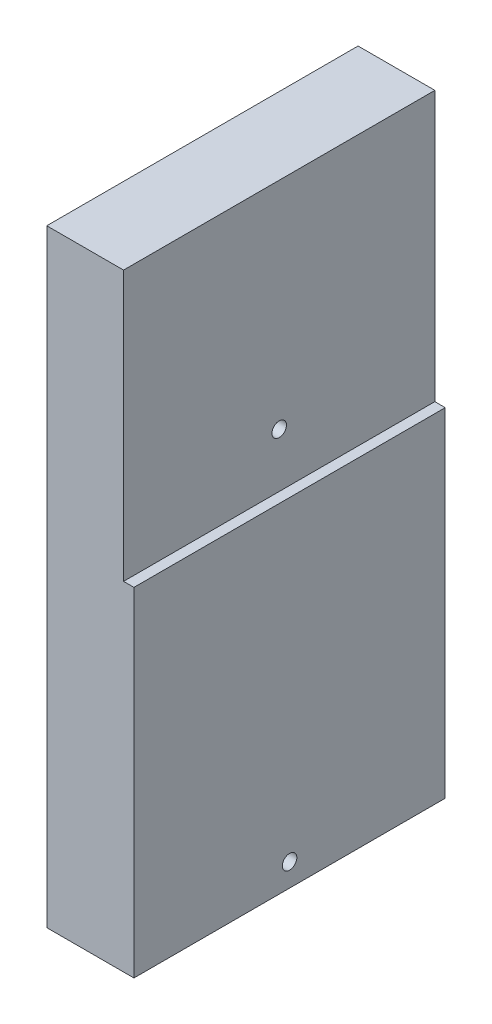
SolidWorks part; units mm, degrees
material "ABS"
ref_plane "Front Plane" through (0, 0, 0) normal (0, 0, 1) x (1, 0, 0)
ref_plane "Top Plane" through (0, 0, 0) normal (0, 1, 0) x (1, 0, 0)
ref_plane "Right Plane" through (0, 0, 0) normal (1, 0, 0) x (0, 0, -1)
sketch "Sketch1" plane through (0, 0, 0) normal (0, 0, 1) x (1, 0, 0)
  line L0 (-20, 159.45) -> (-20, 13)
  line L1 (0, 13) -> (1, 13)
  line L2 (1, 13) -> (1, 94.5)
  line L3 (1, 94.5) -> (-1.5, 94.5)
  line L4 (-1.5, 94.5) -> (-1.5, 159.45)
  line L5 (-1.5, 159.45) -> (-20, 159.45)
  line L6 (-20, 13) -> (0, 13)
  dimension "D2" = 1
  dimension "D3" = 81.5
  dimension "D4" = 2.5
extrude "Boss-Extrude1" add sketch "Sketch1" along normal blind 75
sketch "Sketch2" plane through (1, 0, 0) normal (1, 0, 0) x (0, 0, -1)
  line L0 (-75, 13) -> (0, 13) construction
  line L1 (-75, 13) -> (-75, 94.5) construction
  circle A0 centre (-37.5, 18.5) radius 1.75
  point P0 (-37.5, 18.5)
  point P1 (-37.5, 13)
  dimension "D3" = 3.5
  dimension "D1" = 5.5
  dimension "D2" = 37.5
extrude "Cut-Extrude1" cut sketch "Sketch2" against normal blind 25
sketch "Sketch4" plane through (-1.5, 0, 0) normal (1, 0, 0) x (0, 0, -1)
  line L0 (-75, 94.5) -> (0, 94.5) construction
  line L1 (-75, 94.5) -> (-75, 159.45) construction
  circle A0 centre (-37.5, 107.5) radius 1.75
  point P0 (-37.5, 107.5)
  dimension "D3" = 3.5
  dimension "D1" = 13
  dimension "D2" = 37.5
extrude "Cut-Extrude3" cut sketch "Sketch4" against normal blind 25 contours A0
sketch "Sketch5" plane through (0, 13, 0) normal (0, -1, 0) x (1, 0, 0)
  line L0 (-9.5, 75) -> (-9.5, 0) construction
  line L1 (-20, 75) -> (1, 75) construction
  line L2 (-20, 0) -> (1, 0) construction
  line L3 (-20, 75) -> (-20, 0) construction
  circle A0 centre (-9.5, 50) radius 2.1
  circle A1 centre (-9.5, 25) radius 2.1
  point P6 (-9.5, 50)
  point P7 (-9.5, 25)
  dimension "D3" = 4.2
  dimension "D4" = 4.2
  dimension "D1" = 25
  dimension "D2" = 25
  dimension "D5" = 10.5
extrude "Cut-Extrude4" cut sketch "Sketch5" against normal blind 10
